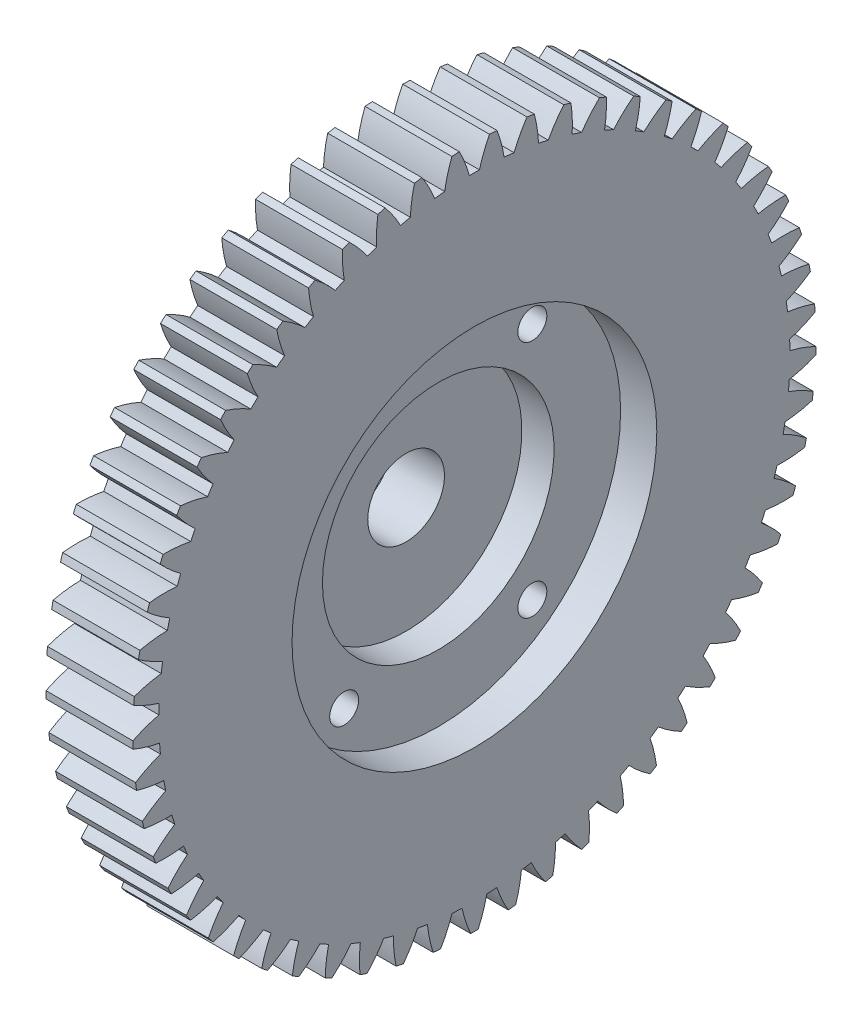
SolidWorks part; units mm, degrees
material "ABS"
ref_plane "Plane1" through (0, 0, 0) normal (0, 0, 1) x (1, 0, 0)
ref_plane "Plane2" through (0, 0, 0) normal (0, 1, 0) x (1, 0, 0)
ref_plane "Plane3" through (0, 0, 0) normal (1, 0, 0) x (0, 0, -1)
sketch "HoldingSke" plane through (0, 0, 0) normal (0, 1, 0) x (1, 0, 0)
  line L0 (0, 0) -> (0.6808, -1.0483)
  line L1 (-15, 0) -> (100, 0) construction
  line L2 (0, 0) -> (-2.1039, 2.3779)
  line L3 (0, 0) -> (-11.863, 4.5341)
  line L4 (0, 0) -> (4.7035, 7.2428)
  line L5 (0, 0) -> (-46.8476, -17.4728)
  line L6 (0, 0) -> (-4.9738, -3.3558)
  line L7 (-2.1039, 2.3779) -> (8.6592, 51.2088)
  line L8 (-76.2, 54.61) -> (-76.1, 54.61)
  line L9 (-71.009, 38.7566) -> (-53.1078, 45.2721)
  line L10 (-76.2, 71.12) -> (104.1128, 71.12)
  line L11 (0, 0) -> (-6, 0)
  line L12 (-76.2, 101.6) -> (-76.17, 101.6)
  line L13 (24.9733, 27.94) -> (52.9518, 28.4284)
  line L14 (24.9733, 27.94) -> (24.9743, 27.94)
  line L15 (24.9733, 27.94) -> (100.4006, 29.5858)
  line L16 (-63.627, -0.8) -> (-12.827, -0.8)
  circle A0 centre (0, 0) radius 0.4
  circle A1 centre (0, 0) radius 21.799
  circle A2 centre (0, 0) radius 37.5
  circle A3 centre (0, 0) radius 0.4
  dimension "MHD" = 43.598
  dimension "Hub_dia" = 75
  dimension "Bore" = 0.8
  dimension "MBD" = 0.8
  dimension "Num_teeth" = 57
  dimension "Pitch" = 1.25
  dimension "Overall_len" = 50
  dimension "Show_teeth" = 57
  dimension "Thickness" = 6
  dimension "OAL" = 50.003
  dimension "T_dim" = 0.1
  dimension "Ap" = 20
  dimension "H" = 19.05
  dimension "Pitch_radius" = 180.3128
  dimension "Width" = 6
  dimension "Backlash" = 0.03
  dimension "Addendum_fac" = 1
  dimension "Dedendum_fac" = 1.25
  dimension "Clearance_fac" = 0.25
  dimension "Dedendum_add" = 0.001
  dimension "Module" = 0.8
sketch "BasProSke" plane through (0, 0, 0) normal (0, 1, 0) x (1, 0, 0)
  line L0 (-10, 0) -> (60, 0) construction
  line L1 (0, 0) -> (0, 23.6)
  line L2 (0, 0) -> (6, 0)
  line L3 (6, 0) -> (6, 23.6)
  line L4 (6, 23.6) -> (0, 23.6)
  dimension "Thickness" = 6
  dimension "Diameter" = 47.2
revolve "Base-Revolve" add sketch "BasProSke" angle 360 about L0
sketch "TooCutSke" plane through (0, 0, 0) normal (1, 0, 0) x (0, 0, -1)
  line L1 (0, 0) -> (0, 107) construction
  line L2 (0, 0) -> (-0.6807, 22.7898) construction
  line L3 (0, 0) -> (-2.5112, 45.5162) construction
  line L4 (-0.6807, 22.7898) -> (-1.2556, 22.7581) construction
  arc A0 (0.345, 21.7963) -> (-0.345, 21.7963) centre (0, 0) ccw
  arc A1 (1.0555, 23.6018) -> (-1.0555, 23.6018) centre (0, 0) ccw
  circle A2 centre (0, 0) radius 22.8 construction
  circle A3 centre (0, 0) radius 21.425 construction
  arc A4 (-0.345, 21.7963) -> (-1.0555, 23.6018) centre (-9.1386, 19.3782) ccw
  arc A5 (1.0555, 23.6018) -> (0.345, 21.7963) centre (9.1386, 19.3782) ccw
  point P12 (0, 0)
  dimension "Root_dia" = 43.598
  dimension "Overcut_dia" = 47.2508
  dimension "Pitch_dia" = 45.6
  dimension "Base_dia" = 42.85
  dimension "Flank_rad" = 9.12
  dimension "Half_ang" = 3.158
  dimension "Half_CT" = 0.5757
extrude "ToothCut" cut sketch "TooCutSke" along normal through all
fillet "Breaks" [suppressed] radius 0.016
fillet "RootFillets" [suppressed] radius 0.201
pattern_circular "TeethCuts" count 57 every 6.316 about axis through (-10, 0, 0) along (1, 0, 0) of "ToothCut", "RootFillets", "Breaks"
sketch "HubNeaOneSke" plane through (0, 0, 0) normal (-1, 0, 0) x (0, 0, 1)
  circle A0 centre (0, 0) radius 21.799
  dimension "Diameter" = 43.598
extrude "HubNearOne" [suppressed] add sketch "HubNeaOneSke" along normal blind 44.003
sketch "HubNeaBotSke" plane through (0, 0, 0) normal (-1, 0, 0) x (0, 0, 1)
  circle A0 centre (0, 0) radius 21.799
  dimension "Diameter" = 43.598
extrude "HubNearBoth" [suppressed] add sketch "HubNeaBotSke" along normal blind 22.0015
ref_plane "FarPln" through (6, 0, 0) normal (1, 0, 0) x (0, 0, -1)
sketch "HubFarSke" plane through (6, 0, 0) normal (1, 0, 0) x (0, 0, -1)
  circle A0 centre (0, 0) radius 21.799
  dimension "Diameter" = 43.598
extrude "HubFar" [suppressed] add sketch "HubFarSke" along normal blind 22.0015
sketch "BorSke" plane through (0, 0, 0) normal (1, 0, 0) x (0, 0, -1)
  circle A0 centre (0, 0) radius 0.4
  dimension "Diameter" = 0.8
extrude "Bore" cut sketch "BorSke" along normal mid plane 100.0061
sketch "KeySke" plane through (0, 0, 0) normal (1, 0, 0) x (0, 0, -1)
  line L0 (-0.05, 0) -> (-0.05, 0.5)
  line L1 (-0.05, 0.5) -> (0.05, 0.5)
  line L2 (0.05, 0.5) -> (0.05, 0)
  line L3 (0, 0) -> (0, 34) construction
  line L4 (-0.05, 0) -> (0.05, 0)
  dimension "Offset" = 0.5
  dimension "Width" = 0.1
extrude "Keyway" [suppressed] cut sketch "KeySke" along normal mid plane 100.0061
pattern_circular "Keyway2" [suppressed] count 2 every 90 about axis through (-10, 0, 0) along (1, 0, 0)
sketch "Esquisse2" plane through (0, 0, 0) normal (0, 1, 0) x (1, 0, 0)
  line L0 (7.2591, 0) -> (-5.6516, 0) construction
  line L1 (-4.4, 0) -> (-4.4, -4.85)
  line L2 (-4.4, -4.85) -> (-0.4, -4.85)
  line L3 (-0.4, -4.85) -> (-0.4, -5.5)
  line L4 (-0.4, -5.5) -> (0, -5.5)
  line L5 (0, -5.1031) -> (0, -6.1732) construction
  line L6 (0, -5.5) -> (0, 0)
  line L7 (0, 0) -> (-4.4, 0)
  dimension "D1" = 9.7
  dimension "D2" = 11
  dimension "D3" = 4
  dimension "D4" = 0.4
revolve "Révolution1" add sketch "Esquisse2" angle 360 about L0
sketch "Esquisse3" plane through (0, 0, 0) normal (0, 1, 0) x (1, 0, 0)
  line L0 (-8.0741, 0) -> (8.9063, 0) construction
  line L1 (-4.4, -4.15) -> (-2.4, -4.15)
  line L2 (-4.4, 4.85) -> (-4.4, -4.85) construction
  line L3 (-2.4, -4.15) -> (-2.4, -2.65)
  line L4 (-2.4, -2.65) -> (1.28, -2.65)
  line L7 (1.28, -2.65) -> (1.28, -8)
  line L8 (1.28, -8) -> (3.5, -8)
  line L9 (3.5, -8) -> (3.5, -12.6)
  line L11 (3.5, -12.6) -> (6, -12.6)
  line L13 (6, -12.6) -> (6, 0)
  line L14 (6, 0) -> (-4.4, 0)
  line L15 (6, -0.4) -> (6, 0.4) construction
  line L16 (-4.4, -4.15) -> (-4.4, 0)
  dimension "D1" = 8.3
  dimension "D2" = 2
  dimension "D3" = 5.68
  dimension "D4" = 5.3
  dimension "D5" = 16
  dimension "D6" = 25.2
  dimension "D7" = 2.5
revolve "Enlèvement de matière-Révolution1" cut sketch "Esquisse3" angle 360 about L0
sketch "Esquisse4" plane through (0, 0, 0) normal (-1, 0, 0) x (0, 0, 1)
  line L0 (-26.1734, 0) -> (25.2971, 0) construction
  line L1 (0, -25.5715) -> (0, 25.5485) construction
  circle A0 centre (-6.5, 8.25) radius 1
  circle A2 centre (-6.5, -8.25) radius 1
  circle A3 centre (6.5, -8.25) radius 1
  circle A4 centre (6.5, 8.25) radius 1
  dimension "D1" = 16.5
  dimension "D3" = 2
  dimension "D2" = 13
extrude "Enlèv. mat.-Extru.2" cut sketch "Esquisse4" against normal up to next
sketch "Esquisse5" plane through (0, 0, 0) normal (-1, 0, 0) x (0, 0, 1)
  circle A0 centre (-6.5, 8.25) radius 2
  circle A1 centre (6.5, 8.25) radius 2
  circle A2 centre (6.5, -8.25) radius 2
  circle A3 centre (-6.5, -8.25) radius 2
  dimension "D1" = 4
extrude "Enlèv. mat.-Extru.3" cut sketch "Esquisse5" against normal blind 1.5
equation "' \"Module@HoldingSke\" = 6.35"
equation "' \"Num_teeth@HoldingSke\" = 12"
equation "' \"Ap@HoldingSke\" =  20"
equation "' \"Ap@HoldingSke\" = 20"
equation "' \"Width@HoldingSke\" = 0.5 * 25.4"
equation "' \"Hub_dia@HoldingSke\"= 1 * 25.4"
equation "' \"Hub_dia@HoldingSke\" = 1 * 25.4"
equation "' \"Overall_len@HoldingSke\" = 1.0 * 25.4"
equation "' \"Bore@HoldingSke\" = 0.75 * 25.4"
equation "' \"T_dim@HoldingSke\" = 0.1 * 25.4"
equation "' \"Width@KeySke\" = 0.25 * 25.4"
equation "' \"Show_teeth@HoldingSke\" = 13"
equation "' \"Backlash@HoldingSke\" = 0.009 * 25.4"
equation "' \"Addendum_fac@HoldingSke\" = 1.0"
equation "' \"Dedendum_fac@HoldingSke\" = 1.25"
equation "' \"Dedendum_add@HoldingSke\" = 0.00005 * 25.4"
equation "' \"Clearance_fac@HoldingSke\" = 0.25"
equation "\"Pitch@HoldingSke\" = 1 / \"Module@HoldingSke\""
equation "\"Overcut_dia@TooCutSke\" = (\"Num_teeth@HoldingSke\" + 2 * \"Addendum_fac@HoldingSke\") / \"Pitch@HoldingSke\" + 0.002 * 25.4"
equation "\"Pitch_dia@TooCutSke\" = \"Num_teeth@HoldingSke\" / \"Pitch@HoldingSke\""
equation "\"Base_dia@TooCutSke\" = \"Num_teeth@HoldingSke\" / \"Pitch@HoldingSke\" * cos((\"Ap@HoldingSke\"  * 3.14159265 / 180))"
equation "\"Root_dia@TooCutSke\" = (\"Num_teeth@HoldingSke\" + 2) / \"Pitch@HoldingSke\" - 2 * (\"Addendum_fac@HoldingSke\" + \"Dedendum_fac@HoldingSke\") / \"Pitch@HoldingSke\" - \"Dedendum_add@HoldingSke\" * 2"
equation "\"Half_ang@TooCutSke\" = 180 / \"Num_teeth@HoldingSke\""
equation "\"Half_CT@TooCutSke\" = \"Num_teeth@HoldingSke\" / \"Pitch@HoldingSke\" * sin((3.14159265 / 2 / \"Num_teeth@HoldingSke\")) / 2 - 7 * \"Backlash@HoldingSke\" / 4"
equation "\"Flank_rad@TooCutSke\" = \"Num_teeth@HoldingSke\" / \"Pitch@HoldingSke\" / 5"
equation "\"Radius@RootFillets\" = \"Clearance_fac@HoldingSke\" / \"Pitch@HoldingSke\" + \"Dedendum_add@HoldingSke\""
equation "\"Break_rad@Breaks\" = 0.02 / \"Pitch@HoldingSke\""
equation "\"Thickness@HoldingSke\" = \"Width@HoldingSke\""
equation "\"OAL@HoldingSke\" = \"Thickness@HoldingSke\""
equation "\"MHD@HoldingSke\" = (\"Num_teeth@HoldingSke\" + 2) / \"Pitch@HoldingSke\" - 2 * (\"Addendum_fac@HoldingSke\" + \"Dedendum_fac@HoldingSke\")  / \"Pitch@HoldingSke\" - \"Dedendum_add@HoldingSke\" * 2"
equation "\"MBD@HoldingSke\" = (\"Num_teeth@HoldingSke\" + 2) / \"Pitch@HoldingSke\" - 2 * (\"Addendum_fac@HoldingSke\" + \"Dedendum_fac@HoldingSke\")  / \"Pitch@HoldingSke\" - \"Dedendum_add@HoldingSke\" * 2 - 0.002 * 25.4"
equation "\"MHD@HoldingSke\" = ((sgn( \"MHD@HoldingSke\" - \"Hub_dia@HoldingSke\" )-1)*( \"MHD@HoldingSke\" - \"Hub_dia@HoldingSke\" ))/-2+ \"Hub_dia@HoldingSke\""
equation "\"MBD@HoldingSke\" = ((sgn( \"MBD@HoldingSke\" - \"Bore@HoldingSke\" )-1)*( \"MBD@HoldingSke\" - \"Bore@HoldingSke\" ))/-2+ \"Bore@HoldingSke\""
equation "\"OAL@HoldingSke\" = ((sgn( \"OAL@HoldingSke\" - \"Overall_len@HoldingSke\" )+1)*( \"OAL@HoldingSke\" - \"Overall_len@HoldingSke\" ))/2 + \"Overall_len@HoldingSke\" + 0.000002 * 25.4"
equation "\"Num_teeth@TeethCuts\" = int( \"Show_teeth@HoldingSke\" ) + 1"
equation "\"Num_teeth@TeethCuts\" = ((sgn( \"Num_teeth@TeethCuts\" - \"Num_teeth@HoldingSke\" )-1)*( \"Num_teeth@TeethCuts\" - \"Num_teeth@HoldingSke\" ))/-2+ \"Num_teeth@HoldingSke\""
equation "\"Num_teeth@TeethCuts\" = ((sgn( \"Num_teeth@TeethCuts\" - 2.0)+1)*( \"Num_teeth@TeethCuts\" - 2.0))/2 +2.0"
equation "\"Angle@TeethCuts\" = 360.0 / \"Num_teeth@HoldingSke\""
equation "\"Diameter@BasProSke\" = (\"Num_teeth@HoldingSke\" + 2 * \"Addendum_fac@HoldingSke\") / \"Pitch@HoldingSke\""
equation "\"Thickness@BasProSke\"  = \"Thickness@HoldingSke\""
equation "' \"Fillet_rad@BasProSke\" =  \"Thickness@HoldingSke\" * 0.05"
equation "' \"Fillet_rad@BasProSke\" = \"Thickness@HoldingSke\" * 0.05"
equation "\"MHD@HoldingSke\" = ((sgn( \"MHD@HoldingSke\" - \"Root_dia@TooCutSke\" )-1)*( \"MHD@HoldingSke\" - \"Root_dia@TooCutSke\" ))/-2+ \"Root_dia@TooCutSke\""
equation "\"Diameter@HubNeaOneSke\" = \"MHD@HoldingSke\""
equation "\"Length@HubNearOne\" = \"OAL@HoldingSke\" - \"Thickness@BasProSke\""
equation "\"Diameter@HubNeaBotSke\" = \"MHD@HoldingSke\""
equation "\"Length@HubNearBoth\" = ( \"OAL@HoldingSke\" - \"Thickness@BasProSke\" ) / 2.0"
equation "\"Thickness@FarPln\" = \"Thickness@BasProSke\""
equation "\"Diameter@HubFarSke\" = \"MHD@HoldingSke\""
equation "\"Length@HubFar\" = ( \"OAL@HoldingSke\" - \"Thickness@BasProSke\" ) / 2.0"
equation "\"Diameter@BorSke\" = \"MBD@HoldingSke\""
equation "\"D1@Bore\" = \"OAL@HoldingSke\" * 2.0"
equation "\"D1@Keyway\" = \"OAL@HoldingSke\" * 2.0"
equation "\"Offset@KeySke\" = \"T_dim@HoldingSke\" + \"MBD@HoldingSke\" / 2.0"
equation "\"D4@Esquisse1\"=\"D3@Esquisse1\"*2"
equation "\"D5@Esquisse1\"=40-\"D4@Esquisse1\""
equation "\"D2@Esquisse1\"=\"D1@Esquisse1\"-5"
